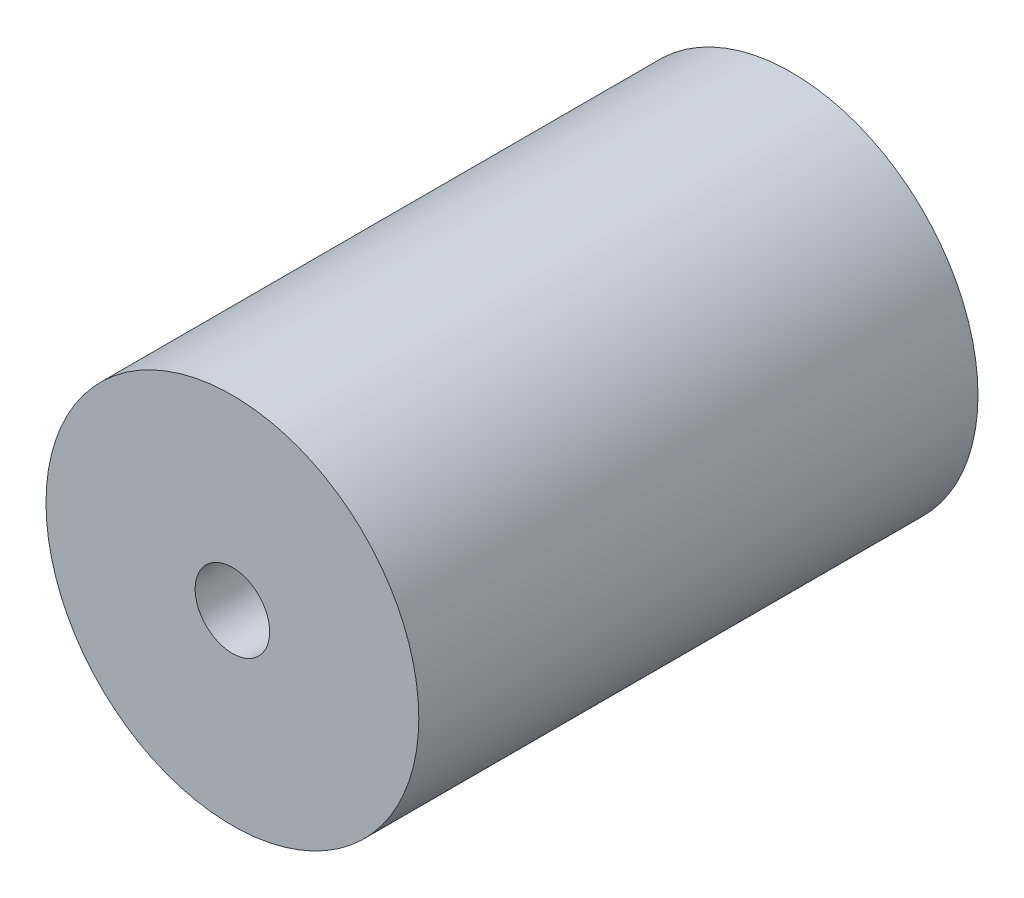
SolidWorks part; units mm, degrees
ref_plane "Přední rovina" through (0, 0, 0) normal (0, 0, 1) x (1, 0, 0)
ref_plane "Horní rovina" through (0, 0, 0) normal (0, 1, 0) x (1, 0, 0)
ref_plane "Pravá rovina" through (0, 0, 0) normal (1, 0, 0) x (0, 0, -1)
sketch "Skica1" plane through (0, 0, 0) normal (0, 0, 1) x (1, 0, 0)
  circle A0 centre (0, 0) radius 20
  dimension "D1" = 40
extrude "Přidat vysunutím1" add sketch "Skica1" along normal blind 60
sketch "Skica2" plane through (0, 0, 60) normal (0, 0, 1) x (1, 0, 0)
  circle A0 centre (0, 0) radius 2.075
  dimension "D1" = 4.15
extrude "Odebrat vysunutím1" cut sketch "Skica2" against normal up to surface (60 mm away) up to face at (20, 0, 0)
sketch "Skica3" plane through (0, 0, 60) normal (0, 0, 1) x (1, 0, 0)
  circle A0 centre (0, 0) radius 4
  dimension "D1" = 8
extrude "Odebrat vysunutím2" cut sketch "Skica3" against normal blind 35
chamfer "Zkosení1" distance 0.5 angle 45 1 edges at (2.075, 0, 25)
